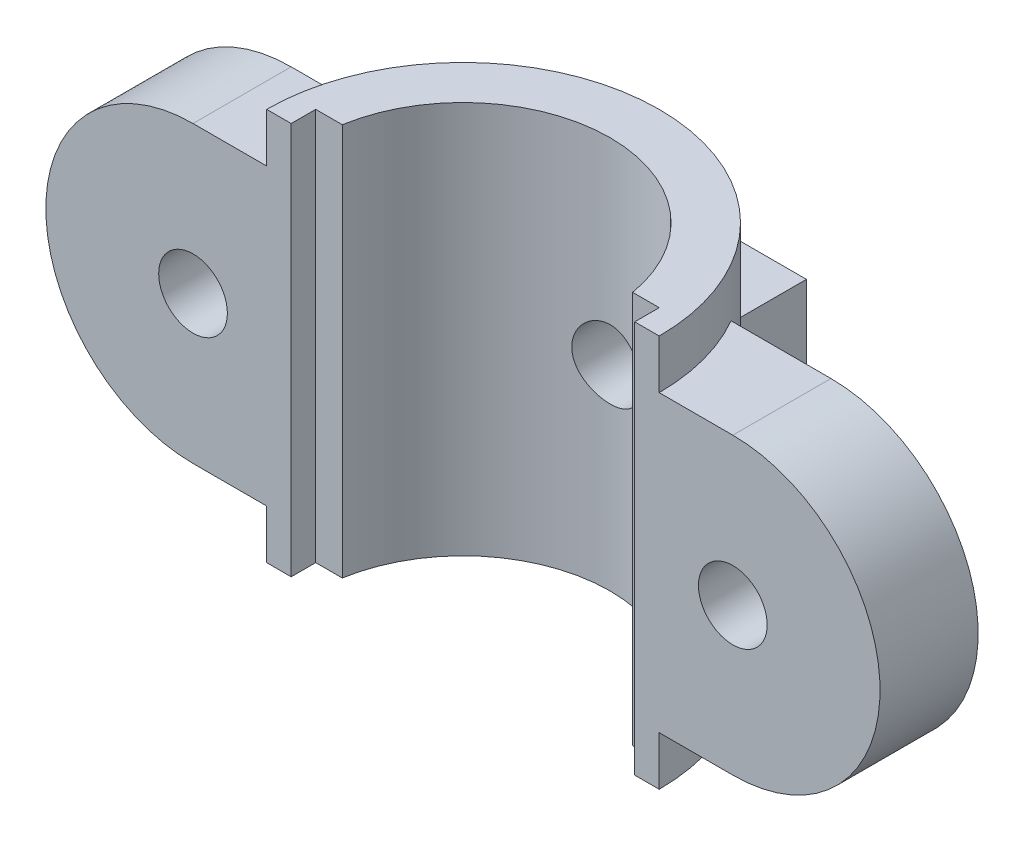
SolidWorks part; units mm, degrees
ref_plane "Front Plane" through (0, 0, 0) normal (0, 0, 1) x (1, 0, 0)
ref_plane "Top Plane" through (0, 0, 0) normal (0, 1, 0) x (1, 0, 0)
ref_plane "Right Plane" through (0, 0, 0) normal (1, 0, 0) x (0, 0, -1)
sketch "Sketch1" plane through (0, 0, 0) normal (0, 0, 1) x (1, 0, 0)
  line L0 (-55, 0) -> (55, 0) construction
  line L1 (-55, 30) -> (55, 30)
  line L2 (-55, -30) -> (55, -30)
  arc A0 (-55, 30) -> (-55, -30) centre (-55, 0) ccw
  arc A1 (55, -30) -> (55, 30) centre (55, 0) ccw
  point P3 (0, 0)
  point P8 (0, 0)
  dimension "D1" = 30
  dimension "D2" = 110
extrude "Boss-Extrude1" add sketch "Sketch1" along normal blind 20
sketch "Sketch5" plane through (0, 0, 0) normal (0, 1, 0) x (1, 0, 0)
  line L0 (55, -20) -> (-55, -20) construction
  line L1 (0, 0) -> (0, -48.2407) construction
  line L2 (-40, -20) -> (40, -20)
  arc A0 (-40, -20) -> (40, -20) centre (0, -20) cw
  point P7 (0, 0)
  point P9 (0, 0)
  point P10 (0, -20)
  dimension "D1" = 40
extrude "Boss-Extrude2" add sketch "Sketch5" along normal mid plane 80
sketch "Sketch6" plane through (0, -40, 0) normal (0, -1, 0) x (-1, 0, 0)
  line L0 (40, -20) -> (-40, -20) construction
  circle A0 centre (0, -20) radius 30
  dimension "D1" = 60
extrude "Cut-Extrude1" cut sketch "Sketch6" against normal up to next
ref_plane "Plane1" through (0, 0, -30) normal (0, 0, -1) x (-1, 0, 0)
sketch "Sketch7" plane through (0, 0, -30) normal (0, 0, -1) x (-1, 0, 0)
  line L1 (-20, 15) -> (20, 15)
  line L2 (-20, 15) -> (-20, -15)
  line L3 (-20, -15) -> (20, -15)
  line L4 (20, 15) -> (20, -15)
  line L5 (-20, 15) -> (20, -15) construction
  line L6 (-20, -15) -> (20, 15) construction
  line L7 (-15, 10) -> (15, 10)
  line L8 (-15, 10) -> (-15, -10)
  line L9 (-15, -10) -> (15, -10)
  line L10 (15, 10) -> (15, -10)
  line L11 (-15, 10) -> (15, -10) construction
  line L12 (-15, -10) -> (15, 10) construction
  point P0 (0, 0)
  point P6 (0, 0)
  point P11 (11.747, -8.8102)
  dimension "D1" = 40
  dimension "D2" = 30
  dimension "D3" = 30
  dimension "D4" = 20
  dimension "D5" = 20
extrude "Boss-Extrude3" add sketch "Sketch7" against normal up to surface (15.359 mm away)
sketch "Sketch8" plane through (0, -40, 0) normal (0, -1, 0) x (-1, 0, 0)
  line L1 (35, -15) -> (-35, -15)
  line L2 (35, -15) -> (35, -20)
  line L3 (35, -20) -> (-35, -20)
  line L4 (-35, -15) -> (-35, -20)
  line L5 (40, -20) -> (30, -20) construction
  line L6 (0, 0) -> (0, -41.6732) construction
  dimension "D1" = 5
  dimension "D2" = 70
extrude "Cut-Extrude2" cut sketch "Sketch8" against normal through all
hole_wizard "Hole1" positions "Sketch10" profile "Sketch11" legacy end condition up to next
sketch "Sketch10" plane through (0, 0, -30) normal (0, 0, -1) x (-1, 0, 0)
  point P0 (0, 0)
sketch "Sketch11" plane through (0, 0, -30) normal (1, 0, 0) x (0, 1, 0)
  line L0 (0, 0) -> (0, 20)
  line L1 (0, 20) -> (7, 20)
  line L2 (7, 20) -> (7, 0)
  line L3 (7, 0) -> (0, 0)
  line L4 (0, 110) -> (0, -10) construction
  dimension "Diameter" = 14
  dimension "Depth" = 20
hole_wizard "Hole2" positions "Sketch14" profile "Sketch15" legacy end condition up to next
sketch "Sketch14" plane through (0, 0, 0) normal (0, 0, -1) x (-1, 0, 0)
  point P0 (-55, 0)
  point P3 (55, 0)
sketch "Sketch15" plane through (55, 0, 0) normal (1, 0, 0) x (0, 1, 0)
  line L0 (0, 0) -> (0, 24.206)
  line L1 (0, 24.206) -> (7, 20)
  line L2 (7, 20) -> (7, 5)
  line L3 (7, 5) -> (10, 5)
  line L4 (10, 0) -> (0, 0)
  line L5 (0, -11.3109) -> (0, 121.1557) construction
  line L6 (0, 24.206) -> (-7, 20) construction
  line L7 (10, 5) -> (10, 0)
  dimension "Depth" = 20
  dimension "Drill Angle" = 118
  dimension "Diameter" = 14
  dimension "C-Bore Diameter" = 20
  dimension "C-Bore Depth" = 5
